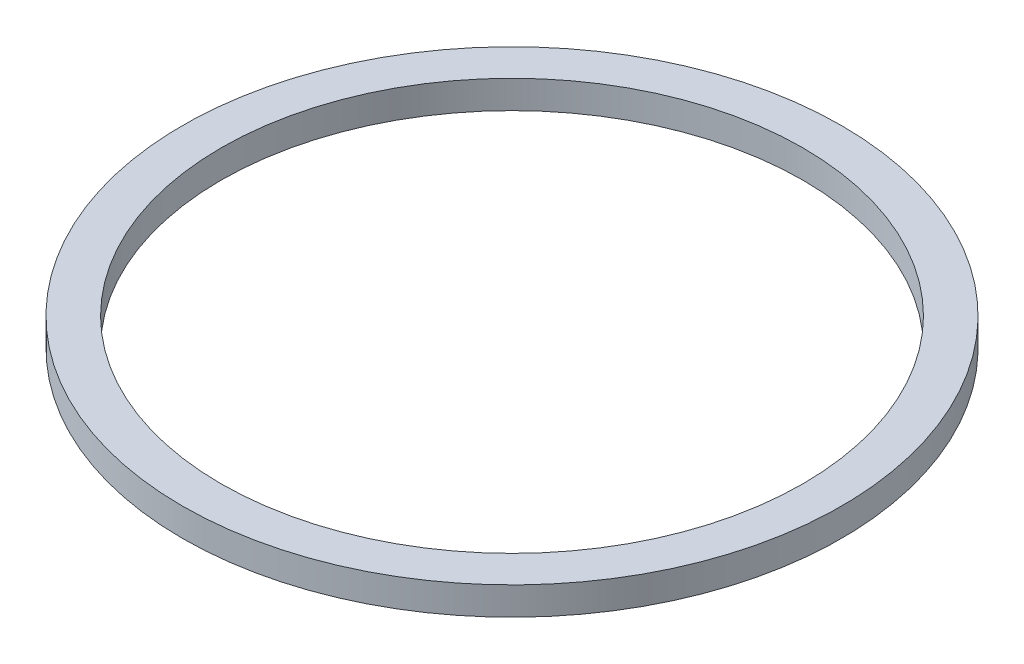
SolidWorks part; units mm, degrees
material "Silicon Rubber"
ref_plane "Front Plane" through (0, 0, 0) normal (0, 0, 1) x (1, 0, 0)
ref_plane "Top Plane" through (0, 0, 0) normal (0, 1, 0) x (1, 0, 0)
ref_plane "Right Plane" through (0, 0, 0) normal (1, 0, 0) x (0, 0, -1)
sketch "Sketch1" plane through (0, 0, 0) normal (0, 1, 0) x (1, 0, 0)
  circle A0 centre (0, 0) radius 11.95
  circle A1 centre (0, 0) radius 10.55
  dimension "D1" = 1.4
  dimension "D2" = 21.1
extrude "Boss-Extrude1" add sketch "Sketch1" along normal blind 1.016
